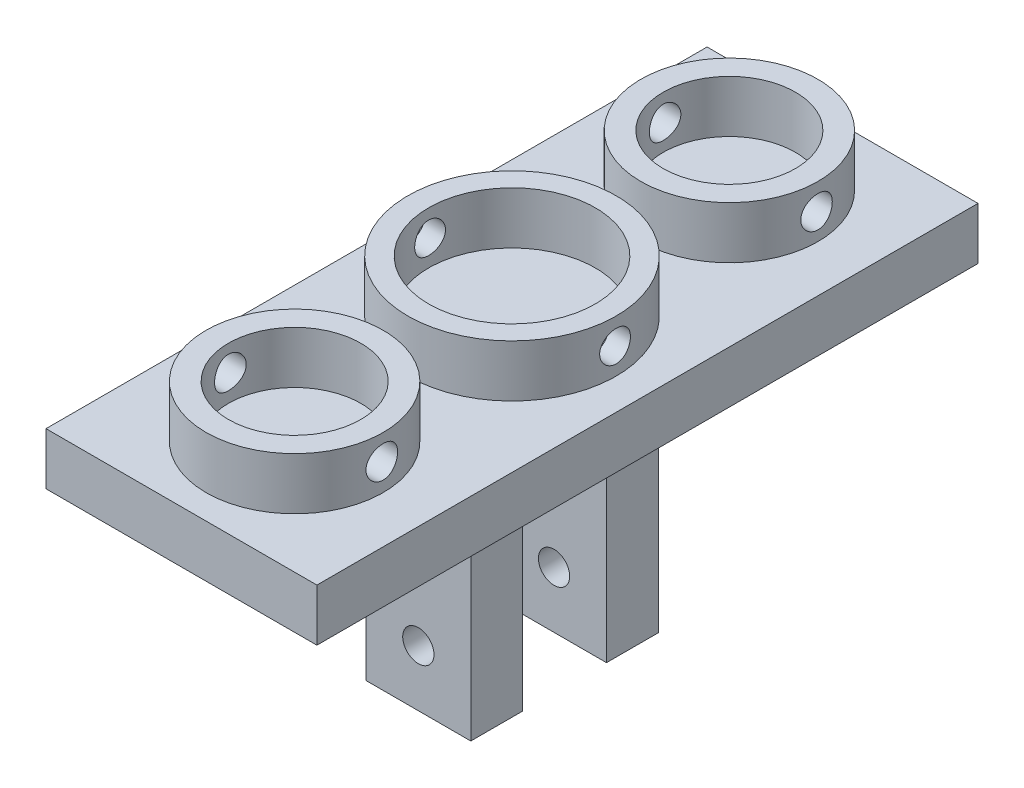
SolidWorks part; units mm, degrees
ref_plane "Alzado" through (0, 0, 0) normal (0, 0, 1) x (1, 0, 0)
ref_plane "Planta" through (0, 0, 0) normal (0, 1, 0) x (1, 0, 0)
ref_plane "Vista lateral" through (0, 0, 0) normal (1, 0, 0) x (0, 0, -1)
sketch "Croquis1" plane through (0, 0, 0) normal (0, 0, 1) x (1, 0, 0)
  line L0 (0, 0) -> (0, -12.5)
  line L1 (0, 0) -> (0, 5.4) construction
  line L2 (0, -12.5) -> (0, -17.9116) construction
  line L3 (-5.0403, 5.4) -> (5.0341, 5.4)
  line L4 (5.0341, -17.9116) -> (-5.0403, -17.9116)
  line L12 (0, 0) -> (-5.0403, 0) construction
  line L13 (0, 0) -> (5.0341, 0) construction
  line L14 (-5.0403, 5.4) -> (-5.0403, -17.9116)
  line L16 (5.0341, 5.4) -> (5.0341, -17.9116)
  circle A0 centre (0, 0) radius 1.5134
  circle A1 centre (0, -12.5) radius 1.5
  dimension "D1" = 3.0267
  dimension "D2" = 3
extrude "Saliente-Extruir1" add sketch "Croquis1" along normal blind 18
sketch "Croquis2" plane through (0, 5.4, 0) normal (0, 1, 0) x (1, 0, 0)
  line L1 (-5.0403, 0) -> (5.0341, 0)
  line L2 (-5.0403, 0) -> (-5.0403, -18)
  line L3 (-5.0403, -18) -> (5.0341, -18)
  line L4 (5.0341, 0) -> (5.0341, -18)
extrude "Saliente-Extruir2" add sketch "Croquis2" along normal blind 5
sketch "Croquis3" plane through (5.0341, 0, 0) normal (1, 0, 0) x (0, 0, -1)
  line L0 (-18, -17.9116) -> (-9, -17.9116) construction
  line L1 (-18, -17.9116) -> (0, -17.9116) construction
  line L2 (-9, -17.9116) -> (-13.0151, -17.9116)
  line L3 (-13.0151, -17.9116) -> (-13.0151, 5.4085)
  line L4 (-13.0151, 5.4085) -> (-4.9767, 5.4085)
  line L5 (-4.9767, 5.4085) -> (-4.9767, -17.9116)
  line L6 (-4.9767, -17.9116) -> (-9, -17.9116)
extrude "Cortar-Extruir1" cut sketch "Croquis3" against normal blind 22
sketch "Croquis4" plane through (0, 10.4, 0) normal (0, 1, 0) x (1, 0, 0)
  line L0 (-5.0403, -9) -> (5.0341, -9) construction
  line L1 (-5.0403, 0) -> (-5.0403, -18) construction
  line L2 (5.0341, -18) -> (5.0341, 0) construction
  line L3 (-0.0031, -9) -> (-0.0031, 3.0153) construction
  line L4 (-0.0031, -9) -> (-0.0031, -21) construction
  line L5 (-0.0031, 3.0153) -> (-0.0031, 15.7153) construction
  line L6 (-0.0031, 15.7153) -> (-0.0031, 22.7153) construction
  line L7 (-0.0031, -21) -> (-0.0031, -33.7) construction
  line L8 (-0.0031, -33.7) -> (-0.0031, -40.7318) construction
  line L9 (-0.0031, 9.3653) -> (6.3469, 9.3653) construction
  line L10 (-0.0031, 9.3653) -> (-6.3531, 9.3653) construction
  line L11 (10.0001, -9) -> (12.9969, -9) construction
  line L12 (12.9969, -9) -> (12.9969, 15.7153) construction
  line L13 (-0.0031, 22.7153) -> (12.9969, 22.7153)
  line L14 (12.9969, 22.7153) -> (12.9969, -40.7318)
  line L15 (-0.0031, 22.7153) -> (-13.0031, 22.7153)
  line L16 (-13.0031, 22.7153) -> (-13.0031, -40.7318)
  line L17 (-13.0031, -40.7318) -> (12.9969, -40.7318)
  dimension "D2" = 12.0153
  dimension "D3" = 12.7
  dimension "D4" = 12.7
extrude "Saliente-Extruir3" add sketch "Croquis4" against normal blind 5
sketch "Croquis5" plane through (0, 10.4, 0) normal (0, 1, 0) x (1, 0, 0)
  line L0 (12.9969, 22.7153) -> (-13.0031, -40.7318) construction
  line L1 (-13.0031, 22.7153) -> (12.9969, -40.7318) construction
  line L2 (-13.0031, -40.7318) -> (12.9969, -40.7318) construction
  circle A0 centre (-0.0031, -9.0083) radius 8
  circle A1 centre (-0.0031, -9.0083) radius 10
  dimension "D1" = 16
  dimension "D2" = 20
extrude "Saliente-Extruir4" add sketch "Croquis5" along normal blind 5
sketch "Croquis7" plane through (0, 0, 0) normal (1, 0, 0) x (0, 0, -1)
  line L0 (-9.0083, 15.4) -> (-9.0083, 12.9008) construction
  line L1 (0.9917, 15.4) -> (-19.0083, 15.4) construction
  circle A0 centre (-9.0083, 12.9008) radius 1.476
extrude "Cortar-Extruir3" cut sketch "Croquis7" against normal blind 14 and the other way blind 33
sketch "Croquis10" plane through (0, 0, -22.7153) normal (0, 0, -1) x (-1, 0, 0)
  line L1 (-12.9969, 10.4) -> (13.0031, 10.4)
  line L2 (-12.9969, 10.4) -> (-12.9969, 5.4)
  line L3 (-12.9969, 5.4) -> (13.0031, 5.4)
  line L4 (13.0031, 10.4) -> (13.0031, 5.4)
sketch "Croquis11" plane through (0, 10.4, 0) normal (0, 1, 0) x (1, 0, 0)
  line L1 (-0.0031, 0.9917) -> (-0.0031, 22.7153) construction
  line L2 (12.9969, 22.7153) -> (-13.0031, 22.7153) construction
  line L3 (-0.0031, 0.9917) -> (-0.0031, 11.8535) construction
  line L4 (-0.0031, 11.8535) -> (-5.311, 11.8535) construction
  circle A2 centre (-0.0031, -9.0083) radius 10 construction
  circle A3 centre (-0.0031, 11.8535) radius 6.35
  circle A4 centre (-0.0031, 11.8535) radius 8.5
  dimension "D1" = 12.7
  dimension "D2" = 17
extrude "Saliente-Extruir6" add sketch "Croquis11" along normal blind 5
sketch "Croquis12" plane through (0, 10.4, 0) normal (0, 1, 0) x (1, 0, 0)
  line L0 (-0.0031, -19.0083) -> (-0.0031, -40.7318) construction
  line L1 (-13.0031, -40.7318) -> (12.9969, -40.7318) construction
  line L2 (-0.0031, -29.87) -> (7.6406, -29.87) construction
  circle A0 centre (-0.0031, -9.0083) radius 10 construction
  circle A1 centre (-0.0031, -9.0083) radius 10 construction
  circle A2 centre (-0.0031, -29.87) radius 6.35
  circle A4 centre (-0.0031, -29.87) radius 8.5
  dimension "D1" = 12.7
  dimension "D2" = 17
extrude "Saliente-Extruir8" add sketch "Croquis12" along normal blind 5
sketch "Croquis13" plane through (0, 0, 0) normal (1, 0, 0) x (0, 0, -1)
  line L0 (11.8535, 15.4) -> (11.8535, 12.8885) construction
  line L1 (20.3535, 15.4) -> (3.3535, 15.4) construction
  line L2 (11.8535, 12.8885) -> (10.5924, 12.8885) construction
  circle A0 centre (11.8535, 12.8885) radius 1.5109
extrude "Cortar-Extruir4" cut sketch "Croquis13" against normal blind 14 and the other way blind 22
sketch "Croquis14" plane through (0, 0, 0) normal (1, 0, 0) x (0, 0, -1)
  line L0 (-29.87, 15.4) -> (-29.87, 12.9637) construction
  line L1 (-23.52, 15.4) -> (-36.22, 15.4) construction
  circle A0 centre (-29.87, 12.9637) radius 1.5178
extrude "Cortar-Extruir5" cut sketch "Croquis14" against normal blind 24 and the other way blind 25
